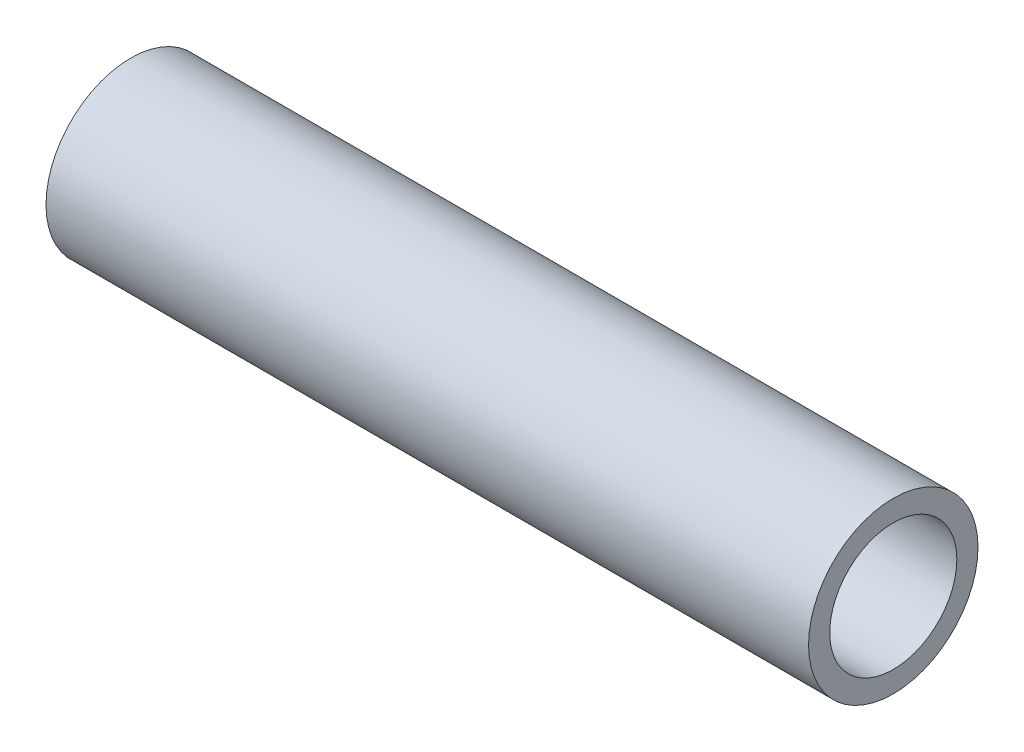
SolidWorks part; units mm, degrees
material "Alumina"
ref_plane "Front Plane" through (0, 0, 0) normal (0, 0, 1) x (1, 0, 0)
ref_plane "Top Plane" through (0, 0, 0) normal (0, 1, 0) x (1, 0, 0)
ref_plane "Right Plane" through (0, 0, 0) normal (1, 0, 0) x (0, 0, -1)
sketch "Sketch1" plane through (0, 0, 0) normal (1, 0, 0) x (0, 0, -1)
  circle A0 centre (0, 0) radius 12.7
  circle A1 centre (0, 0) radius 9.525
  dimension "D1" = 25.4
  dimension "D2" = 19.05
extrude "Alumina Tube Extrude" add sketch "Sketch1" along normal blind 114.3
equation "\"ID\" = .75"
equation "\"OD\" = 1"
equation "\"D2@Sketch1\"=\"ID\""
equation "\"D1@Sketch1\"=\"OD\""
equation "\"L\"= 4.5"
equation "\"D1@Alumina Tube Extrude\"=\"L\""
